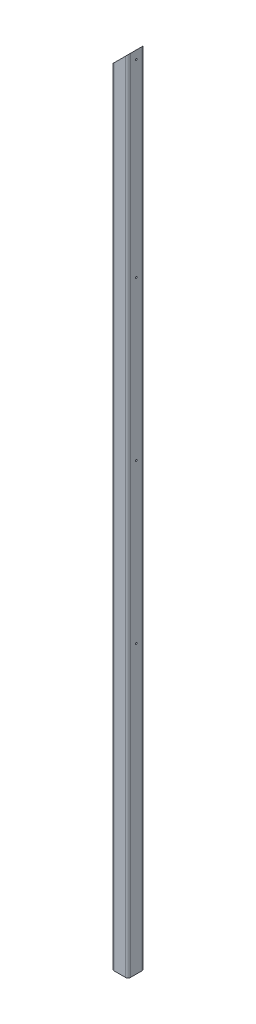
SolidWorks part; units mm, degrees
ref_plane "Front Plane" through (0, 0, 0) normal (0, 0, 1) x (1, 0, 0)
ref_plane "Top Plane" through (0, 0, 0) normal (0, 1, 0) x (1, 0, 0)
ref_plane "Right Plane" through (0, 0, 0) normal (1, 0, 0) x (0, 0, -1)
sketch "Sketch1" plane through (0, 0, 0) normal (0, 0, 1) x (1, 0, 0)
  line L0 (0, 0) -> (0, 1920)
  dimension "D1" = 1920
other "Tube (square) 40 X 40 X 3.2(1)"
ref_plane "Plane1" through (0, 0, 0) normal (0, 1, 0) x (-1, 0, 0)
sketch "Sketch15" plane through (0, 0, 0) normal (0, 1, 0) x (-1, 0, 0)
  line L0 (-13.6, -16.8) -> (13.6, -16.8)
  line L1 (-16.8, -13.6) -> (-16.8, 13.6)
  line L2 (13.6, 16.8) -> (-13.6, 16.8)
  line L3 (16.8, 13.6) -> (16.8, -13.6)
  line L4 (-13.6, -20) -> (13.6, -20)
  line L5 (-20, -13.6) -> (-20, 13.6)
  line L6 (13.6, 20) -> (-13.6, 20)
  line L7 (20, 13.6) -> (20, -13.6)
  line L8 (-20, 0) -> (-16.8, 0) construction
  line L9 (-16.8, 0) -> (16.8, 0) construction
  line L10 (16.8, 0) -> (20, 0) construction
  line L12 (0, 20) -> (0, 16.8) construction
  line L13 (0, 16.8) -> (0, -16.8) construction
  line L14 (0, -16.8) -> (0, -20) construction
  arc A0 (20, 13.6) -> (13.6, 20) centre (13.6, 13.6) ccw
  arc A1 (13.6, -20) -> (20, -13.6) centre (13.6, -13.6) ccw
  arc A2 (-20, -13.6) -> (-13.6, -20) centre (-13.6, -13.6) ccw
  arc A3 (-13.6, 20) -> (-20, 13.6) centre (-13.6, 13.6) ccw
  arc A4 (-13.6, 16.8) -> (-16.8, 13.6) centre (-13.6, 13.6) ccw
  arc A5 (16.8, 13.6) -> (13.6, 16.8) centre (13.6, 13.6) ccw
  arc A6 (13.6, -16.8) -> (16.8, -13.6) centre (13.6, -13.6) ccw
  arc A7 (-16.8, -13.6) -> (-13.6, -16.8) centre (-13.6, -13.6) ccw
  point P2 (-20, 20)
  point P33 (-20, -20)
  point P34 (20, -20)
  point P36 (20, 20)
  point P37 (0, 0)
  dimension "D1" = 6.4
  dimension "Thickness" = 3.2
  dimension "V_leg" = 40
  dimension "H_leg" = 40
ref_plane "Plane2" through (0, 0, -20) normal (0, 0, -1) x (-1, 0, 0)
sketch "Sketch13" plane through (0, 0, -20) normal (0, 0, -1) x (-1, 0, 0)
  line L2 (20, 1920) -> (20, 0) construction
  line L3 (20, 1920) -> (20, 1880)
  line L4 (-13.6, 1920) -> (13.6, 1920) construction
  line L5 (-20, 1920) -> (20, 1920)
  line L9 (20, 1880) -> (-20, 1920)
  line L10 (20, 1920) -> (20, 1880)
  dimension "D1" = 40
extrude "Cut-Extrude1" cut sketch "Sketch13" against normal through all contours L9 L3 L5
ref_plane "Plane3" through (20, 0, 0) normal (1, 0, 0) x (0, 0, -1)
sketch "Sketch16" plane through (20, 0, 0) normal (1, 0, 0) x (0, 0, -1)
  line L0 (-13.6, 1920) -> (13.6, 1920) construction
  line L1 (-13.6, 1920) -> (13.6, 1920) construction
  line L2 (-13.6, 1900) -> (13.6, 1900) construction
  line L3 (-13.6, 1447) -> (13.6, 1447) construction
  line L4 (-13.6, 1067) -> (13.6, 1067) construction
  line L5 (-13.6, 687) -> (13.6, 687) construction
  circle A0 centre (0, 1900) radius 2
  circle A1 centre (0, 1447) radius 2
  circle A2 centre (0, 1067) radius 2
  circle A3 centre (0, 687) radius 2
  dimension "D4" = 4
  dimension "D5" = 1233
  dimension "D1" = 20
  dimension "D2" = 453
  dimension "D3" = 833
extrude "Cut-Extrude2" cut sketch "Sketch16" against normal blind 3
ref_plane "Plane4" through (0, 0, -20) normal (0, 0, -1) x (-1, 0, 0)
sketch "Sketch17" plane through (0, 0, -20) normal (0, 0, -1) x (-1, 0, 0)
  line L0 (-13.6, 0) -> (13.6, 0) construction
  line L1 (-13.6, 0) -> (13.6, 0)
  line L2 (-13.6, 687) -> (13.6, 687) construction
  circle A0 centre (0, 687) radius 2
  circle A1 centre (0, 937) radius 2
  dimension "D2" = 250
  dimension "D1" = 687
extrude "Cut-Extrude3" cut sketch "Sketch17" against normal blind 3 contours A0 | A1
